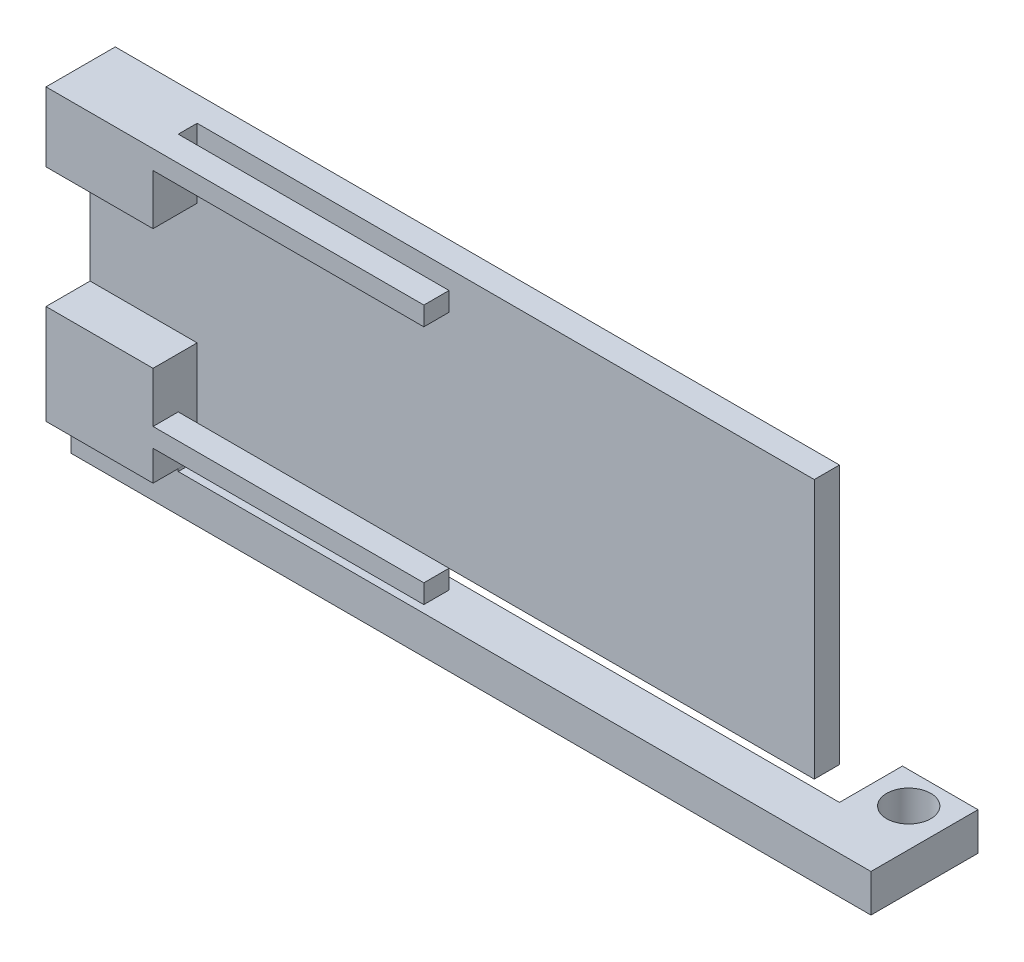
SolidWorks part; units mm, degrees
ref_plane "Plano frontal" through (0, 0, 0) normal (0, 0, 1) x (1, 0, 0)
ref_plane "Plano superior" through (0, 0, 0) normal (0, 1, 0) x (1, 0, 0)
ref_plane "Plano direito" through (0, 0, 0) normal (1, 0, 0) x (0, 0, -1)
sketch "Esboço1" plane through (0, 0, 0) normal (0, 0, 1) x (1, 0, 0)
  line L1 (-19.5835, 7.9869) -> (32.9165, 7.9869)
  line L2 (-19.5835, 7.9869) -> (-19.5835, -12.6131)
  line L3 (-19.5835, -12.6131) -> (32.9165, -12.6131)
  line L4 (32.9165, 7.9869) -> (32.9165, -12.6131)
  dimension "D1" = 20.6
  dimension "D2" = 52.5
extrude "Ressalto-extrusão1" add sketch "Esboço1" along normal blind 2
sketch "Esboço2" plane through (0, 0, 2) normal (0, 0, 1) x (1, 0, 0)
  line L0 (-19.5835, -12.6131) -> (32.9165, -12.6131) construction
  line L1 (-19.5835, 7.9869) -> (-16.0835, 7.9869)
  line L2 (-19.5835, 7.9869) -> (-19.5835, -12.6131)
  line L3 (-19.5835, -12.6131) -> (-16.0835, -12.6131)
  line L4 (-16.0835, 7.9869) -> (-16.0835, -12.6131)
  dimension "D1" = 3.5
extrude "Ressalto-extrusão2" add sketch "Esboço2" along normal blind 3.5
sketch "Esboço3" plane through (0, 0, 5.5) normal (0, 0, 1) x (1, 0, 0)
  line L0 (-19.5835, 7.9869) -> (-19.5835, -12.6131) construction
  line L1 (-19.5835, 2.4869) -> (-16.0835, 2.4869)
  line L2 (-19.5835, 2.4869) -> (-19.5835, -7.1131)
  line L3 (-19.5835, -7.1131) -> (-16.0835, -7.1131)
  line L4 (-16.0835, 2.4869) -> (-16.0835, -7.1131)
  line L5 (-16.0835, -12.6131) -> (-16.0835, 7.9869) construction
  line L6 (-16.0835, 7.9869) -> (-19.5835, 7.9869) construction
  line L7 (-19.5835, -12.6131) -> (-16.0835, -12.6131) construction
  point P12 (-17.8335, -12.6131)
  dimension "D1" = 5.5
  dimension "D2" = 5.5
extrude "Corte-extrusão1" cut sketch "Esboço3" against normal blind 3.5
sketch "Esboço4" plane through (-16.0835, 0, 0) normal (1, 0, 0) x (0, 0, -1)
  line L1 (-5.5, 7.9869) -> (-3.5, 7.9869)
  line L2 (-5.5, 7.9869) -> (-5.5, 6.4869)
  line L3 (-5.5, 6.4869) -> (-3.5, 6.4869)
  line L4 (-3.5, 7.9869) -> (-3.5, 6.4869)
  line L6 (-5.5, -12.6131) -> (-3.5, -12.6131)
  line L7 (-5.5, -12.6131) -> (-5.5, -11.1131)
  line L8 (-5.5, -11.1131) -> (-3.5, -11.1131)
  line L9 (-3.5, -12.6131) -> (-3.5, -11.1131)
  line L10 (-2, 2.4869) -> (-2, 7.9869) construction
  dimension "D1" = 1.5
  dimension "D2" = 1.5
  dimension "D3" = 1.5
  dimension "D4" = 2
extrude "Ressalto-extrusão3" add sketch "Esboço4" along normal blind 21.5
sketch "Esboço5" plane through (0, 0, 2) normal (0, 0, 1) x (1, 0, 0)
  line L1 (-19.5835, 7.9869) -> (-24.5835, 7.9869)
  line L2 (-19.5835, 7.9869) -> (-19.5835, -12.6131)
  line L4 (-24.5835, 7.9869) -> (-24.5835, -12.6131)
  line L9 (-19.5835, -12.6131) -> (-16.0835, -12.6131)
  line L10 (-24.5835, -12.6131) -> (-24.5835, -15.0131)
  line L11 (-24.5835, -15.0131) -> (-16.0835, -15.0131)
  line L12 (-16.0835, -12.6131) -> (-16.0835, -15.0131)
  dimension "D2" = 5
  dimension "D3" = 8.5
  dimension "D4" = 2.4
extrude "Ressalto-extrusão4" add sketch "Esboço5" against normal blind 2
sketch "Esboço9" plane through (0, 0, 2) normal (0, 0, 1) x (1, 0, 0)
  line L0 (-19.5835, -7.1131) -> (-24.5835, -7.1131)
  line L1 (-19.5835, 2.4869) -> (-24.5835, 2.4869)
  line L2 (-19.5835, 2.4869) -> (-19.5835, 7.9869)
  line L3 (-19.5835, 7.9869) -> (-24.5835, 7.9869)
  line L4 (-24.5835, 2.4869) -> (-24.5835, 7.9869)
  line L5 (-24.5835, 7.9869) -> (-24.5835, -15.0131) construction
  line L6 (-24.5835, -7.1131) -> (-24.5835, -15.0131)
  line L7 (-24.5835, -15.0131) -> (-16.0835, -15.0131)
  line L8 (-16.0835, -15.0131) -> (-16.0835, -12.6131)
  line L9 (-16.0835, -12.6131) -> (-19.5835, -12.6131)
  line L10 (-19.5835, -12.6131) -> (-19.5835, -7.1131)
extrude "Ressalto-extrusão8" add sketch "Esboço9" along normal through all
sketch "Esboço10" plane through (0, 0, 3.5) normal (0, 0, -1) x (-1, 0, 0)
  line L5 (16.0835, -15.2131) -> (-38.9165, -15.2131)
  line L6 (24.5835, -15.2131) -> (24.5835, -18.2131)
  line L7 (24.5835, -18.2131) -> (-38.9165, -18.2131)
  line L8 (-38.9165, -15.2131) -> (-38.9165, -18.2131)
  line L9 (24.5835, 7.9869) -> (24.5835, -15.0131) construction
  line L12 (24.5835, -15.2131) -> (24.5835, -15.0131)
  line L13 (16.0835, -15.0131) -> (16.0835, -15.2131)
  line L14 (16.0835, -15.0131) -> (24.5835, -15.0131)
  line L15 (-32.9165, -12.6131) -> (-32.9165, 7.9869) construction
  dimension "D1" = 3
  dimension "D2" = 0.2
  dimension "D3" = 0.2
  dimension "D4" = 6
extrude "Ressalto-extrusão9" add sketch "Esboço10" along normal through all separate body
sketch "Esboço11" plane through (0, 0, 0) normal (0, 0, -1) x (-1, 0, 0)
  line L0 (16.0835, -15.2131) -> (-38.9165, -15.2131) construction
  line L1 (24.5835, -18.2131) -> (16.0835, -18.2131)
  line L2 (24.5835, -18.2131) -> (24.5835, -15.2131)
  line L3 (24.5835, -15.2131) -> (16.0835, -15.2131)
  line L4 (16.0835, -18.2131) -> (16.0835, -15.2131)
  line L5 (-38.9165, -18.2131) -> (-32.9165, -18.2131)
  line L6 (-38.9165, -18.2131) -> (-38.9165, -15.2131)
  line L7 (-38.9165, -15.2131) -> (-32.9165, -15.2131)
  line L8 (-32.9165, -18.2131) -> (-32.9165, -15.2131)
extrude "Ressalto-extrusão10" add sketch "Esboço11" along normal blind 5
sketch "Esboço12" plane through (0, -15.2131, 0) normal (0, 1, 0) x (1, 0, 0)
  line L0 (-24.5835, 5) -> (-16.0835, 0) construction
  line L1 (-16.0835, 0) -> (-16.0835, 5) construction
  line L2 (-16.0835, 5) -> (-24.5835, 0) construction
  line L3 (-24.5835, 0) -> (32.9165, 5) construction
  line L4 (32.9165, 5) -> (38.9165, 0) construction
  line L6 (38.9165, 5) -> (38.9165, -3.5) construction
  line L7 (32.9165, 0) -> (38.9165, 5) construction
  circle A0 centre (35.9165, 2.5) radius 1.75
  circle A1 centre (-20.3335, 2.5) radius 1.75
  point P12 (37.0832, 0)
  point P13 (37.0832, 0)
  point P21 (37.1305, 0)
  point P22 (38.9165, 0)
extrude "Corte-extrusão2" cut sketch "Esboço12" against normal blind 5
